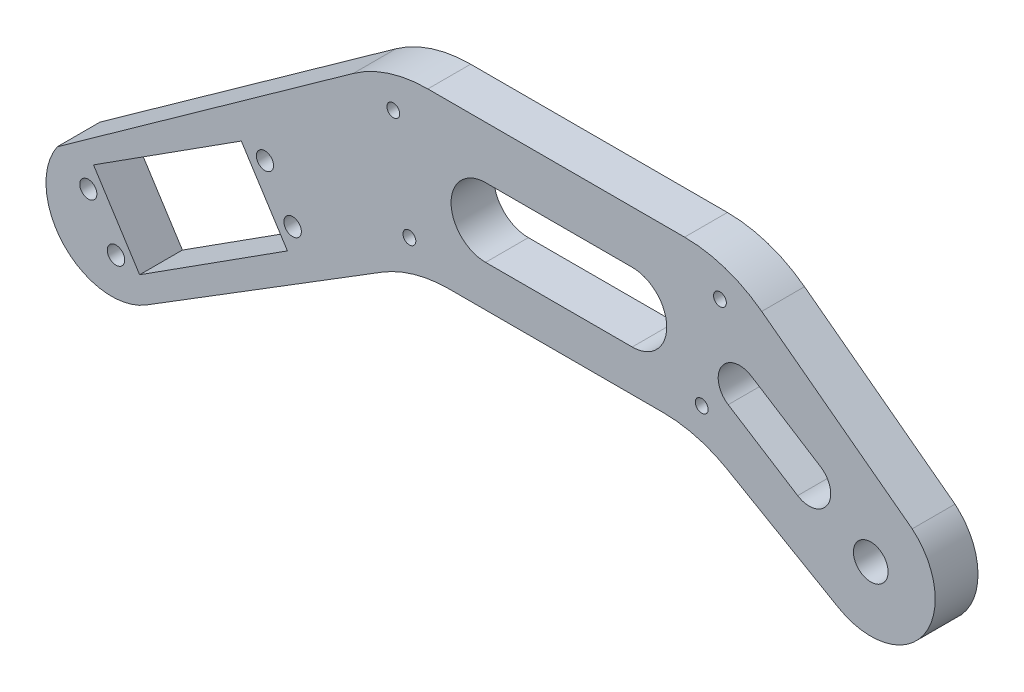
SolidWorks part; units mm, degrees
ref_plane "Front Plane" through (0, 0, 0) normal (0, 0, 1) x (1, 0, 0)
ref_plane "Top Plane" through (0, 0, 0) normal (0, 1, 0) x (1, 0, 0)
ref_plane "Right Plane" through (0, 0, 0) normal (1, 0, 0) x (0, 0, -1)
sketch "Sketch1" plane through (0, 0, 0) normal (0, 0, 1) x (1, 0, 0)
  line L0 (-36.5059, 38) -> (23.4941, 38)
  line L1 (41.5151, 31.9842) -> (76.6804, 5.5622)
  line L2 (-31.5059, 0) -> (18.4941, 0)
  line L3 (33.4898, -4.0167) -> (59.4731, -19.0124)
  line L4 (-53.9471, 32.4091) -> (-123.1061, -17.0079)
  line L5 (-47.3246, -4.5095) -> (-102.3151, -38.6351)
  line L6 (99.3935, 38) -> (45.1336, -39.4912) construction
  line L7 (-112.4053, 38) -> (99.3935, 38) construction
  line L8 (-112.4053, 38) -> (-112.4053, -39.4912) construction
  line L9 (-112.4053, -39.4912) -> (99.3935, -39.4912) construction
  line L10 (99.3935, 38) -> (99.3935, -39.4912) construction
  line L11 (-114.6339, -16.4384) -> (-80.0963, 5.6557)
  line L12 (-6.5059, 38) -> (-6.5059, -39.4912) construction
  line L13 (-45.6636, 36.5681) -> (-39.7303, -1.1494) construction
  line L14 (32.9934, 36.4563) -> (26.2563, -1.0216) construction
  line L15 (66.9996, -5.9709) -> (29.6249, 17.7174) construction
  line L16 (29.6249, 17.7174) -> (-42.697, 17.7094) construction
  line L17 (-110.4027, -25.6027) -> (-42.697, 17.7094) construction
  line L18 (-80.0963, 5.6557) -> (-69.3187, -11.1919)
  line L19 (-69.3187, -11.1919) -> (-103.8563, -33.2861)
  line L20 (-103.8563, -33.2861) -> (-114.6339, -16.4384)
  line L21 (-97.3651, -5.3914) -> (-86.5875, -22.239) construction
  line L22 (-114.6339, -16.4384) -> (-115.3599, -16.9028) construction
  line L23 (-103.1806, -32.8538) -> (-109.7278, -37.0421) construction
  line L24 (-23.0158, 17.7115) -> (11.2516, 17.7153) construction
  line L25 (-23.0167, 25.7773) -> (11.2507, 25.7811)
  line L26 (-23.0149, 9.6458) -> (11.2525, 9.6496)
  line L27 (36.3755, 13.4388) -> (52.6086, 3.1502) construction
  line L28 (39.069, 17.6886) -> (55.3022, 7.4)
  line L29 (33.6819, 9.189) -> (49.9151, -1.0997)
  arc A0 (33.4898, -4.0167) -> (18.4941, 0) centre (18.4941, -30) ccw
  arc A1 (41.5151, 31.9842) -> (23.4941, 38) centre (23.4941, 8) ccw
  arc A2 (-36.5059, 38) -> (-53.9471, 32.4091) centre (-36.5059, 8) ccw
  arc A3 (-31.5059, 0) -> (-47.3246, -4.5095) centre (-31.5059, -30) ccw
  arc A4 (59.4731, -19.0124) -> (76.6804, 5.5622) centre (66.9996, -5.9709) ccw
  arc A5 (-102.3151, -38.6351) -> (-123.1061, -17.0079) centre (-110.4027, -25.6027) cw
  circle A6 centre (66.9996, -5.9709) radius 4.05
  circle A7 centre (-44.5758, 29.6531) radius 1.5
  circle A8 centre (-115.8479, -21.9635) radius 2.0045
  circle A9 centre (-109.3814, -32.0721) radius 2.0395
  circle A10 centre (-68.1047, -5.6669) radius 2.0395
  circle A11 centre (-74.5712, 4.4417) radius 2.0045
  circle A12 centre (-40.8181, 5.7656) radius 1.5
  circle A13 centre (31.7549, 29.5668) radius 1.5
  circle A14 centre (27.4948, 5.868) radius 1.5
  arc A15 (-23.0167, 25.7773) -> (-23.0149, 9.6458) centre (-23.0158, 17.7115) ccw
  arc A16 (11.2525, 9.6496) -> (11.2507, 25.7811) centre (11.2516, 17.7153) ccw
  arc A17 (39.069, 17.6886) -> (33.6819, 9.189) centre (36.3755, 13.4388) ccw
  arc A18 (49.9151, -1.0997) -> (55.3022, 7.4) centre (52.6086, 3.1502) ccw
  point P13 (-6.0432, -4.9781)
  point P22 (33.5087, 38)
  point P62 (-5.8821, 17.7134)
  point P69 (44.4921, 8.2945)
  dimension "D1" = 38
  dimension "D4" = 30
  dimension "D6" = 30
  dimension "D3" = 30
  dimension "D5" = 30
  dimension "D20" = 8.1
  dimension "D22" = 3
  dimension "D21" = 3
  dimension "D27" = 3
  dimension "D28" = 3
  dimension "D2" = 54
  dimension "D7" = 30
  dimension "D8" = 30
  dimension "D9" = 55
  dimension "D10" = 85
  dimension "D11" = 25
  dimension "D12" = 30
  dimension "D13" = 25
  dimension "D14" = 25
  dimension "D15" = 41
  dimension "D16" = 30
  dimension "D17" = 20
  dimension "D18" = 10
  dimension "D19" = 38
  dimension "D23" = 4
  dimension "D24" = 4
  dimension "D25" = 4
  dimension "D26" = 4
  dimension "D29" = 7
  dimension "D30" = 7
  dimension "D31" = 7
  dimension "D32" = 7
extrude "Boss-Extrude1" add sketch "Sketch1" along normal blind 10
